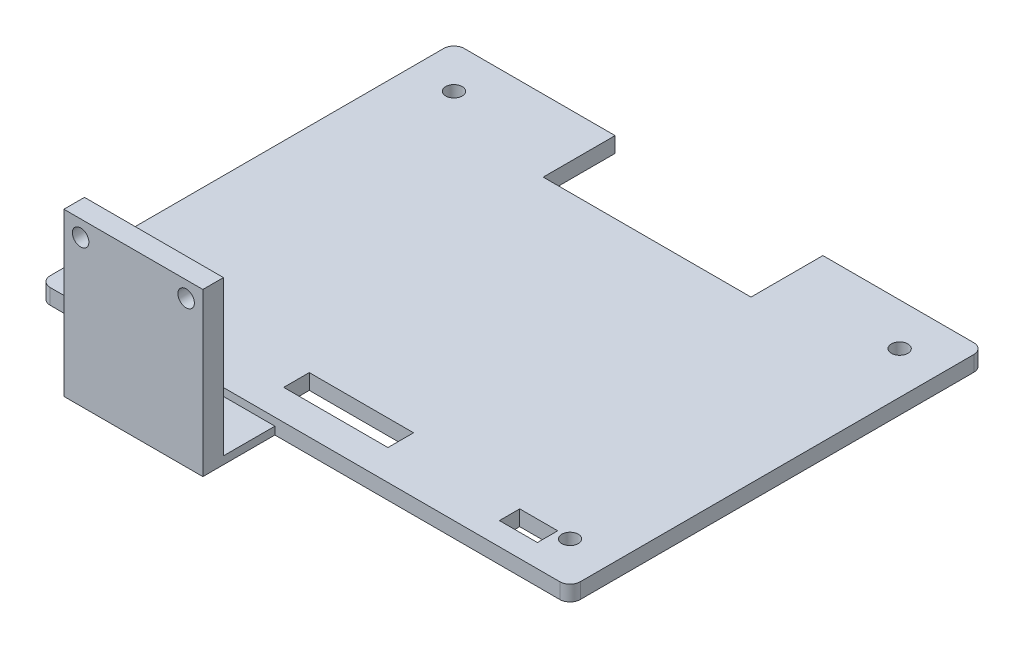
SolidWorks part; units mm, degrees
ref_plane "前视基准面" through (0, 0, 0) normal (0, 0, 1) x (1, 0, 0)
ref_plane "上视基准面" through (0, 0, 0) normal (0, 1, 0) x (1, 0, 0)
ref_plane "右视基准面" through (0, 0, 0) normal (1, 0, 0) x (0, 0, -1)
sketch "草图1" plane through (0, 0, 0) normal (0, 1, 0) x (1, 0, 0)
  line L0 (-51.5, 40.2204) -> (-43.3, 32.0204) construction
  line L1 (49.5, -40.2204) -> (-49.5, -40.2204)
  line L2 (51.5, -38.2204) -> (51.5, 38.2204)
  line L3 (49.5, 40.2204) -> (-49.5, 40.2204)
  line L4 (-51.5, -38.2204) -> (-51.5, 38.2204)
  line L5 (51.5, -40.2204) -> (-51.5, 40.2204) construction
  line L6 (51.5, 40.2204) -> (-51.5, -40.2204) construction
  line L7 (20.1874, 26.2491) -> (-20.1874, 26.2491)
  line L8 (20.1874, 26.2491) -> (20.1874, 36.5704)
  line L10 (-20.1874, 26.2491) -> (-20.1874, 36.5704)
  line L11 (20.1874, 26.2491) -> (-20.1874, 36.5704) construction
  line L12 (20.1874, 36.5704) -> (-20.1874, 26.2491) construction
  line L13 (0, 31.4098) -> (0, -40.2204) construction
  line L14 (51.5, 0) -> (-51.5, 0)
  line L15 (33.3536, -35.8039) -> (40.7411, -35.8039)
  line L16 (-10.0207, -29.3673) -> (10.2401, -29.3673)
  line L17 (-10.0207, -29.3673) -> (-10.0207, -34.3411)
  line L18 (-10.0207, -34.3411) -> (10.2401, -34.3411)
  line L19 (10.2401, -29.3673) -> (10.2401, -34.3411)
  line L20 (-33.3536, -31.8542) -> (-40.7411, -31.8542)
  line L21 (-33.3536, -31.8542) -> (-33.3536, -35.8039)
  line L22 (-33.3536, -35.8039) -> (-40.7411, -35.8039)
  line L23 (-40.7411, -31.8542) -> (-40.7411, -35.8039)
  line L24 (40.7411, -31.8542) -> (40.7411, -35.8039)
  line L25 (33.3536, -31.8542) -> (40.7411, -31.8542)
  line L26 (33.3536, -31.8542) -> (33.3536, -35.8039)
  line L27 (-20.1874, 36.5704) -> (-20.1874, 40.2204)
  line L28 (-20.1874, 40.2204) -> (20.1874, 40.2204)
  line L29 (20.1874, 40.2204) -> (20.1874, 36.5704)
  circle A0 centre (-43.3, 32.0204) radius 1.6
  circle A1 centre (43.3, 32.0204) radius 1.6
  circle A2 centre (43.3, -32.0204) radius 1.6
  circle A3 centre (-43.3, -32.0204) radius 1.6
  arc A4 (-49.5, -40.2204) -> (-51.5, -38.2204) centre (-49.5, -38.2204) cw
  arc A5 (49.5, -40.2204) -> (51.5, -38.2204) centre (49.5, -38.2204) ccw
  arc A6 (51.5, 38.2204) -> (49.5, 40.2204) centre (49.5, 38.2204) ccw
  arc A7 (-49.5, 40.2204) -> (-51.5, 38.2204) centre (-49.5, 38.2204) ccw
  point P0 (0, 0)
  point P6 (0, 31.4098)
  point P18 (0, 0)
  dimension "D4" = 2
  dimension "D2" = 86.6
  dimension "D1" = 103
  dimension "D3" = 45
extrude "凸台-拉伸1" add sketch "草图1" along normal blind 3
ref_plane "基准面1" through (0, 0, 40.2204) normal (0, 0, 1) x (1, 0, 0)
sketch "草图2" plane through (0, 0, 40.2204) normal (0, 0, 1) x (1, 0, 0)
  line L6 (49.5, 0) -> (-49.5, 0) construction
  line L7 (-32.8465, 1.5) -> (-5.8465, 1.5)
  line L8 (-32.8465, 1.5) -> (-32.8465, 0)
  line L9 (-32.8465, 0) -> (-5.8465, 0)
  line L10 (-5.8465, 1.5) -> (-5.8465, 0)
extrude "凸台-拉伸2" add sketch "草图2" along normal blind 14 contours L8 L7 L10 L9
sketch "草图4" plane through (0, 1.5, 0) normal (0, 1, 0) x (1, 0, 0)
  line L0 (-19.3465, -54.2204) -> (-19.3465, -50.2204) construction
  line L5 (-32.8465, -54.2204) -> (-5.8465, -54.2204) construction
  line L6 (-32.8465, -54.2204) -> (-32.8465, -40.2204) construction
  line L17 (-5.8465, -54.2204) -> (-32.8465, -54.2204)
  line L18 (-5.8465, -54.2204) -> (-5.8465, -50.2204)
  line L19 (-5.8465, -50.2204) -> (-32.8465, -50.2204)
  line L20 (-32.8465, -54.2204) -> (-32.8465, -50.2204)
  line L21 (-5.8465, -54.2204) -> (-32.8465, -50.2204) construction
  line L22 (-5.8465, -50.2204) -> (-32.8465, -54.2204) construction
  point P4 (-19.3465, -52.2204)
  dimension "D1" = 4
extrude "凸台-拉伸3" add sketch "草图4" along normal blind 30 contours L18 L17 L20 L19
sketch "草图5" plane through (0, 0, 54.2204) normal (0, 0, 1) x (1, 0, 0)
  line L2 (-5.8465, 31.5) -> (-32.8465, 31.5) construction
  line L3 (-19.3465, 31.5) -> (-19.3465, 3.1595) construction
  circle A1 centre (-29.5965, 28.3813) radius 1.6
  circle A2 centre (-9.0965, 28.3813) radius 1.6
  dimension "D1" = 20.5
extrude "切除-拉伸1" cut sketch "草图5" against normal blind 30 contours A1 | A2
